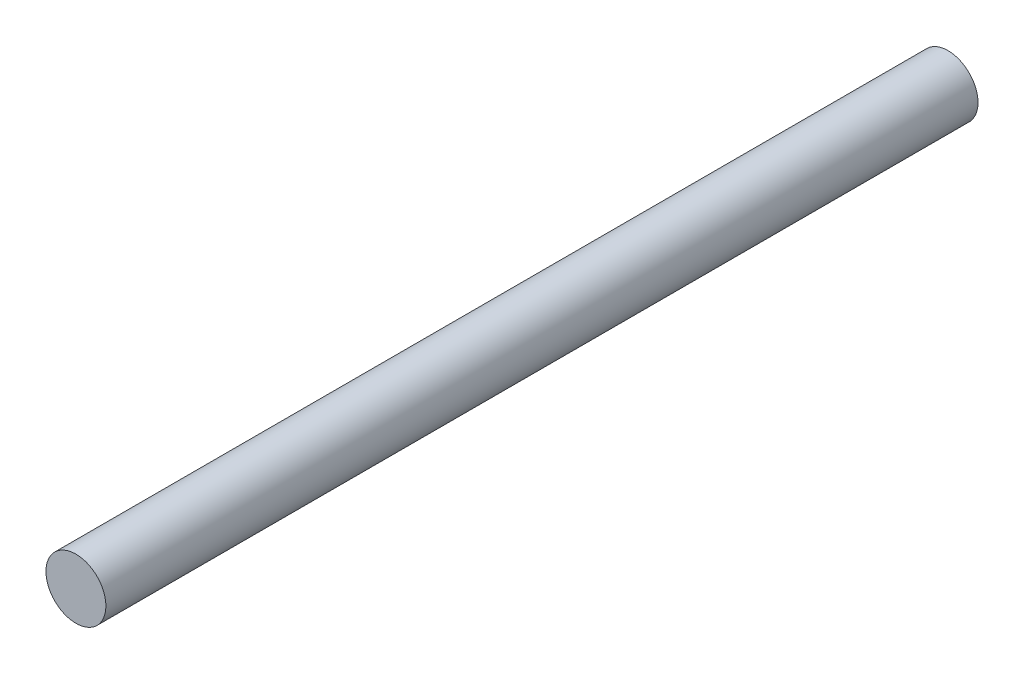
SolidWorks part; units mm, degrees
material "1023 Carbon Steel Sheet (SS)"
ref_plane "Front Plane" through (0, 0, 0) normal (0, 0, 1) x (1, 0, 0)
ref_plane "Top Plane" through (0, 0, 0) normal (0, 1, 0) x (1, 0, 0)
ref_plane "Right Plane" through (0, 0, 0) normal (1, 0, 0) x (0, 0, -1)
sketch "Sketch1" plane through (0, 0, 0) normal (0, 0, 1) x (1, 0, 0)
  circle A0 centre (0, 0) radius 5.5
extrude "Boss-Extrude1" add sketch "Sketch1" along normal blind 160
